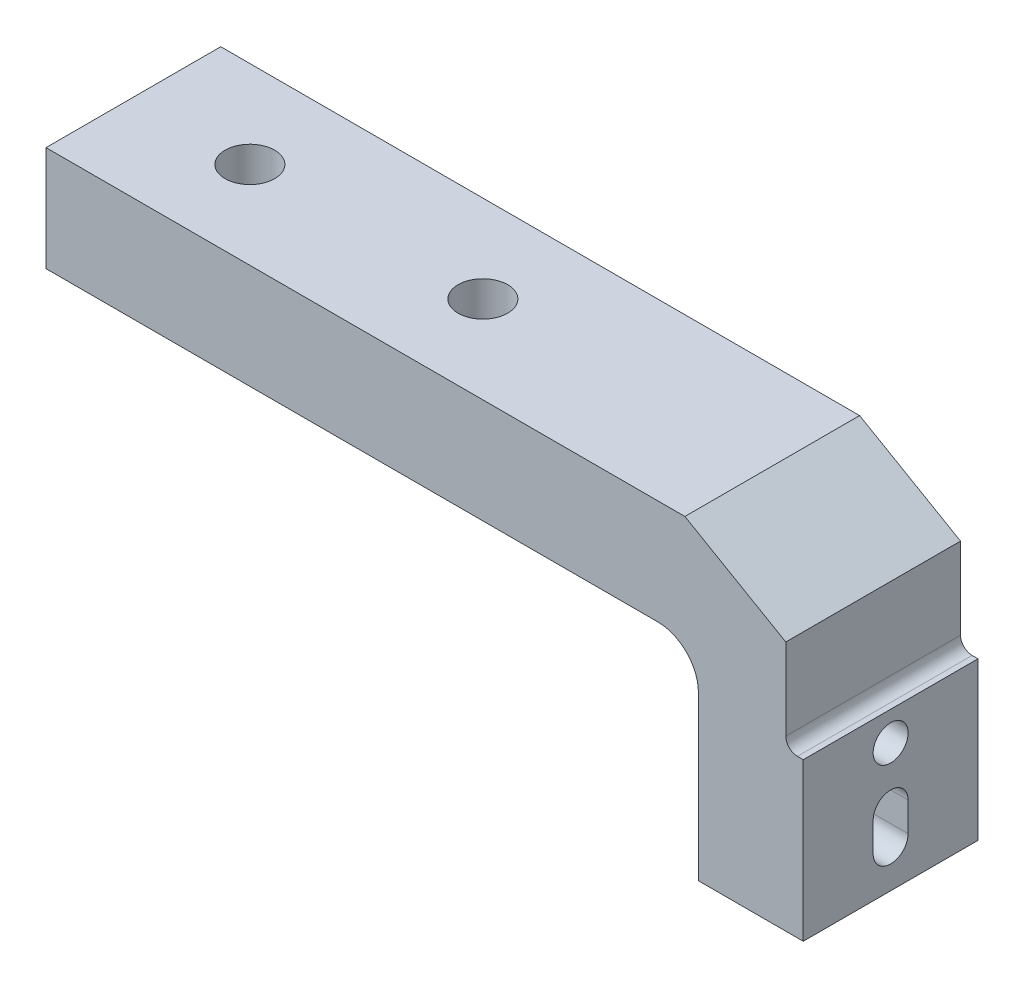
SolidWorks part; units mm, degrees
material "1023 Carbon Steel Sheet (SS)"
ref_plane "Front Plane" through (0, 0, 0) normal (0, 0, 1) x (1, 0, 0)
ref_plane "Top Plane" through (0, 0, 0) normal (0, 1, 0) x (1, 0, 0)
ref_plane "Right Plane" through (0, 0, 0) normal (1, 0, 0) x (0, 0, -1)
sketch "Sketch1" plane through (0, 0, 0) normal (0, 0, 1) x (1, 0, 0)
  line L0 (0, 0) -> (0, 27)
  line L1 (0, 27) -> (-3, 27)
  line L2 (-3, 27) -> (-3, 53)
  line L5 (-3, 53) -> (-130, 53)
  line L6 (-130, 53) -> (-130, 35)
  line L7 (-130, 35) -> (-18, 35)
  line L10 (-18, 35) -> (-18, 0)
  line L11 (-18, 0) -> (0, 0)
  dimension "D1" = 27
  dimension "D2" = 3
  dimension "D6" = 18
  dimension "D9" = 18
  dimension "D10" = 35
extrude "Boss-Extrude1" add sketch "Sketch1" along normal mid plane 30
sketch "Sketch2" plane through (0, 0, 0) normal (1, 0, 0) x (0, 0, -1)
  line L0 (0, 0) -> (0, 23.8182) construction
  line L1 (-15, 27) -> (15, 27) construction
  line L2 (0, 12) -> (0, 7) construction
  line L3 (3, 12) -> (3, 7)
  line L4 (-3, 12) -> (-3, 7)
  circle A1 centre (0, 22) radius 3
  arc A2 (3, 12) -> (-3, 12) centre (0, 12) ccw
  arc A3 (-3, 7) -> (3, 7) centre (0, 7) ccw
  point P9 (0, 9.5)
  dimension "D3" = 6
  dimension "D4" = 10
  dimension "D1" = 3
  dimension "D2" = 5
  dimension "D5" = 5
extrude "Cut-Extrude1" cut sketch "Sketch2" against normal up to next
sketch "Sketch3" plane through (0, 35, 0) normal (0, -1, 0) x (1, 0, 0)
  line L0 (0, 0) -> (-155.1137, 0) construction
  line L1 (-130, 15) -> (-130, -15) construction
  circle A0 centre (-110, 0) radius 4.25
  circle A1 centre (-70, 0) radius 4.25
  dimension "D3" = 8.5
  dimension "D4" = 8.5
  dimension "D1" = 40
  dimension "D2" = 20
extrude "Cut-Extrude2" cut sketch "Sketch3" against normal blind 30
fillet "Fillet3" radius 7 1 edges at (-18, 35, 0)
chamfer "Chamfer1" distance 10 angle 60 1 edges at (-3, 53, 0)
fillet "Fillet4" radius 2 1 edges at (-3, 27, 0)
